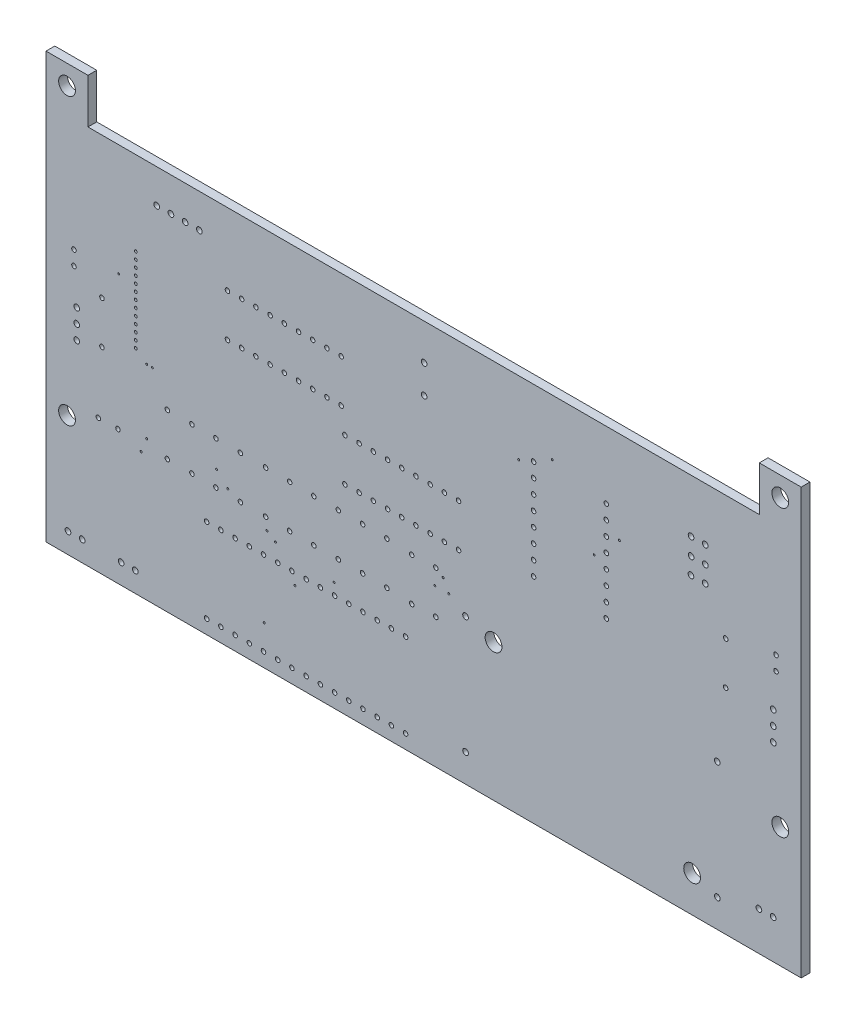
SolidWorks part; units mm, degrees
ref_plane "Plan de face" through (0, 0, 0) normal (0, 0, 1) x (1, 0, 0)
ref_plane "Plan de dessus" through (0, 0, 0) normal (0, 1, 0) x (1, 0, 0)
ref_plane "Plan de droite" through (0, 0, 0) normal (1, 0, 0) x (0, 0, -1)
ref_plane "Plan1" through (0, 0, 1.57) normal (0, 0, 1) x (1, 0, 0)
sketch "Esquisse1" plane through (0, 0, 1.57) normal (0, 0, 1) x (1, 0, 0)
  line L0 (135, 0) -> (135, 76)
  line L1 (135, 76) -> (0, 76)
  line L2 (0, 76) -> (0, 0)
  line L3 (0, 0) -> (135, 0)
  circle A0 centre (115.5, 6.5) radius 1.5
  circle A1 centre (80, 24.5) radius 1.5
  circle A2 centre (3.76, 72.5) radius 1.5
  circle A3 centre (3.76, 21.5) radius 1.5
  circle A4 centre (131.26, 21.5) radius 1.5
  circle A5 centre (131.26, 72.5) radius 1.5
  circle A6 centre (120, 26) radius 0.508
  circle A7 centre (75, 26) radius 0.508
  circle A8 centre (130.5, 45.23) radius 0.4065
  circle A9 centre (5, 45.23) radius 0.4065
  circle A10 centre (16.05, 38) radius 0.25
  circle A11 centre (16.05, 40.5) radius 0.25
  circle A12 centre (16.05, 43) radius 0.25
  circle A13 centre (16.05, 45.5) radius 0.25
  circle A14 centre (16.05, 48) radius 0.25
  circle A15 centre (16.05, 50.5) radius 0.25
  circle A16 centre (16.05, 53) radius 0.25
  circle A17 centre (55.97, 43.26) radius 0.4065
  circle A18 centre (61.05, 43.26) radius 0.4065
  circle A19 centre (66.13, 43.26) radius 0.4065
  circle A20 centre (71.21, 43.26) radius 0.4065
  circle A21 centre (73.75, 35.64) radius 0.4065
  circle A22 centre (68.67, 35.64) radius 0.4065
  circle A23 centre (63.59, 35.64) radius 0.4065
  circle A24 centre (58.51, 35.64) radius 0.4065
  circle A25 centre (53.43, 35.64) radius 0.4065
  circle A26 centre (34.98, 55.13) radius 0.4065
  circle A27 centre (40.06, 55.13) radius 0.4065
  circle A28 centre (45.14, 55.13) radius 0.4065
  circle A29 centre (50.22, 55.13) radius 0.4065
  circle A30 centre (52.76, 47.51) radius 0.4065
  circle A31 centre (47.68, 47.51) radius 0.4065
  circle A32 centre (42.6, 47.51) radius 0.4065
  circle A33 centre (37.52, 47.51) radius 0.4065
  circle A34 centre (32.44, 47.51) radius 0.4065
  circle A35 centre (19.79, 61.96) radius 0.508
  circle A36 centre (24.87, 61.96) radius 0.508
  circle A37 centre (121.5, 45.81) radius 0.4065
  circle A38 centre (10, 42.81) radius 0.4065
  circle A39 centre (56.59, 23.44) radius 0.4065
  circle A40 centre (52.25, 23.44) radius 0.4065
  circle A41 centre (47.87, 23.42) radius 0.4065
  circle A42 centre (43.55, 23.47) radius 0.4065
  circle A43 centre (39.26, 23.54) radius 0.4065
  circle A44 centre (34.75, 23.56) radius 0.4065
  circle A45 centre (30.38, 23.62) radius 0.4065
  circle A46 centre (26.09, 23.65) radius 0.4065
  circle A47 centre (69.68, 23.25) radius 0.4065
  circle A48 centre (65.37, 23.09) radius 0.4065
  circle A49 centre (60.93, 23.37) radius 0.4065
  circle A50 centre (39, 7) radius 0.175
  circle A51 centre (130, 39.07) radius 0.508
  circle A52 centre (130, 33.99) radius 0.508
  circle A53 centre (5.49, 36.51) radius 0.508
  circle A54 centre (12.86, 23.91) radius 0.4
  circle A55 centre (67.59, 61.54) radius 0.508
  circle A56 centre (28.72, 17.5) radius 0.4065
  circle A57 centre (33.8, 17.5) radius 0.4065
  circle A58 centre (38.88, 17.5) radius 0.4065
  circle A59 centre (43.96, 17.5) radius 0.4065
  circle A60 centre (49.04, 17.5) radius 0.4065
  circle A61 centre (54.12, 17.5) radius 0.4065
  circle A62 centre (59.2, 17.5) radius 0.4065
  circle A63 centre (64.28, 17.5) radius 0.4065
  circle A64 centre (61.74, 2.5) radius 0.4065
  circle A65 centre (56.66, 2.5) radius 0.4065
  circle A66 centre (51.58, 2.5) radius 0.4065
  circle A67 centre (46.5, 2.5) radius 0.4065
  circle A68 centre (41.42, 2.5) radius 0.4065
  circle A69 centre (36.34, 2.5) radius 0.4065
  circle A70 centre (31.26, 2.5) radius 0.4065
  circle A71 centre (87.16, 38.24) radius 0.4065
  circle A72 centre (87.16, 43.32) radius 0.4065
  circle A73 centre (87.16, 48.4) radius 0.4065
  circle A74 centre (87.16, 53.48) radius 0.4065
  circle A75 centre (100.16, 56.02) radius 0.4065
  circle A76 centre (100.16, 50.94) radius 0.4065
  circle A77 centre (100.16, 45.86) radius 0.4065
  circle A78 centre (100.16, 40.78) radius 0.4065
  circle A79 centre (13.43, 3.57) radius 0.508
  circle A80 centre (3.93, 3.64) radius 0.508
  circle A81 centre (117.85, 58.52) radius 0.508
  circle A82 centre (117.86, 55.46) radius 0.508
  circle A83 centre (117.83, 52.49) radius 0.508
  circle A84 centre (129.98, 6.93) radius 0.508
  circle A85 centre (72, 28) radius 0.175
  circle A86 centre (19, 36.5) radius 0.175
  circle A87 centre (51.5, 19.5) radius 0.175
  circle A88 centre (39.5, 21.5) radius 0.175
  circle A89 centre (41, 20.5) radius 0.175
  circle A90 centre (30.5, 26.5) radius 0.175
  circle A91 centre (32.5, 24.5) radius 0.175
  circle A92 centre (44.5, 15.5) radius 0.175
  circle A93 centre (69.5, 28) radius 0.175
  circle A94 centre (102.5, 51.5) radius 0.175
  circle A95 centre (71, 30) radius 0.175
  circle A96 centre (98, 47) radius 0.175
  circle A97 centre (17, 22.5) radius 0.175
  circle A98 centre (18, 25) radius 0.175
  circle A99 centre (84.5, 55) radius 0.175
  circle A100 centre (90.5, 58) radius 0.175
  circle A101 centre (13, 48) radius 0.175
  circle A102 centre (18, 36.5) radius 0.175
  circle A103 centre (127.44, 6.93) radius 0.508
  circle A104 centre (115.29, 52.49) radius 0.508
  circle A105 centre (115.32, 55.46) radius 0.508
  circle A106 centre (115.31, 58.52) radius 0.508
  circle A107 centre (6.47, 3.64) radius 0.508
  circle A108 centre (15.97, 3.57) radius 0.508
  circle A109 centre (100.16, 38.24) radius 0.4065
  circle A110 centre (100.16, 43.32) radius 0.4065
  circle A111 centre (100.16, 48.4) radius 0.4065
  circle A112 centre (100.16, 53.48) radius 0.4065
  circle A113 centre (87.16, 56.02) radius 0.4065
  circle A114 centre (87.16, 50.94) radius 0.4065
  circle A115 centre (87.16, 45.86) radius 0.4065
  circle A116 centre (87.16, 40.78) radius 0.4065
  circle A117 centre (28.72, 2.5) radius 0.4065
  circle A118 centre (33.8, 2.5) radius 0.4065
  circle A119 centre (38.88, 2.5) radius 0.4065
  circle A120 centre (43.96, 2.5) radius 0.4065
  circle A121 centre (49.04, 2.5) radius 0.4065
  circle A122 centre (54.12, 2.5) radius 0.4065
  circle A123 centre (59.2, 2.5) radius 0.4065
  circle A124 centre (64.28, 2.5) radius 0.4065
  circle A125 centre (61.74, 17.5) radius 0.4065
  circle A126 centre (56.66, 17.5) radius 0.4065
  circle A127 centre (51.58, 17.5) radius 0.4065
  circle A128 centre (46.5, 17.5) radius 0.4065
  circle A129 centre (41.42, 17.5) radius 0.4065
  circle A130 centre (36.34, 17.5) radius 0.4065
  circle A131 centre (31.26, 17.5) radius 0.4065
  circle A132 centre (67.59, 56.46) radius 0.508
  circle A133 centre (9.36, 23.91) radius 0.4
  circle A134 centre (5.49, 39.05) radius 0.508
  circle A135 centre (5.49, 33.97) radius 0.508
  circle A136 centre (130, 36.53) radius 0.508
  circle A137 centre (21.69, 23.68) radius 0.4065
  circle A138 centre (21.69, 31.3) radius 0.4065
  circle A139 centre (60.93, 30.99) radius 0.4065
  circle A140 centre (65.37, 30.71) radius 0.4065
  circle A141 centre (69.68, 30.87) radius 0.4065
  circle A142 centre (26.09, 31.27) radius 0.4065
  circle A143 centre (30.38, 31.24) radius 0.4065
  circle A144 centre (34.75, 31.18) radius 0.4065
  circle A145 centre (39.26, 31.16) radius 0.4065
  circle A146 centre (43.55, 31.09) radius 0.4065
  circle A147 centre (47.87, 31.04) radius 0.4065
  circle A148 centre (52.25, 31.06) radius 0.4065
  circle A149 centre (56.59, 31.06) radius 0.4065
  circle A150 centre (10, 35.19) radius 0.4065
  circle A151 centre (121.5, 38.19) radius 0.4065
  circle A152 centre (22.33, 61.96) radius 0.508
  circle A153 centre (27.41, 61.96) radius 0.508
  circle A154 centre (34.98, 47.51) radius 0.4065
  circle A155 centre (40.06, 47.51) radius 0.4065
  circle A156 centre (45.14, 47.51) radius 0.4065
  circle A157 centre (50.22, 47.51) radius 0.4065
  circle A158 centre (52.76, 55.13) radius 0.4065
  circle A159 centre (47.68, 55.13) radius 0.4065
  circle A160 centre (42.6, 55.13) radius 0.4065
  circle A161 centre (37.52, 55.13) radius 0.4065
  circle A162 centre (32.44, 55.13) radius 0.4065
  circle A163 centre (55.97, 35.64) radius 0.4065
  circle A164 centre (61.05, 35.64) radius 0.4065
  circle A165 centre (66.13, 35.64) radius 0.4065
  circle A166 centre (71.21, 35.64) radius 0.4065
  circle A167 centre (73.75, 43.26) radius 0.4065
  circle A168 centre (68.67, 43.26) radius 0.4065
  circle A169 centre (63.59, 43.26) radius 0.4065
  circle A170 centre (58.51, 43.26) radius 0.4065
  circle A171 centre (53.43, 43.26) radius 0.4065
  circle A172 centre (16.05, 51.75) radius 0.25
  circle A173 centre (16.05, 49.25) radius 0.25
  circle A174 centre (16.05, 46.75) radius 0.25
  circle A175 centre (16.05, 44.25) radius 0.25
  circle A176 centre (16.05, 41.75) radius 0.25
  circle A177 centre (16.05, 39.25) radius 0.25
  circle A178 centre (5, 47.77) radius 0.4065
  circle A179 centre (130.5, 47.77) radius 0.4065
  circle A180 centre (75, 5) radius 0.508
  circle A181 centre (120, 5) radius 0.508
extrude "Boss.-Extru.1" add sketch "Esquisse1" against normal blind 1.57
sketch "Esquisse2" plane through (0, 0, 1.57) normal (0, 0, 1) x (1, 0, 0)
  line L0 (135, 76) -> (0, 76) construction
  line L1 (127.5, 76) -> (7.5, 76)
  line L2 (127.5, 76) -> (127.5, 68)
  line L3 (127.5, 68) -> (7.5, 68)
  line L4 (7.5, 76) -> (7.5, 68)
  point P6 (67.5, 76)
  point P8 (67.5, 76)
  dimension "D1" = 120
  dimension "D2" = 8
extrude "Enlèv. mat.-Extru.1" cut sketch "Esquisse2" against normal through all
